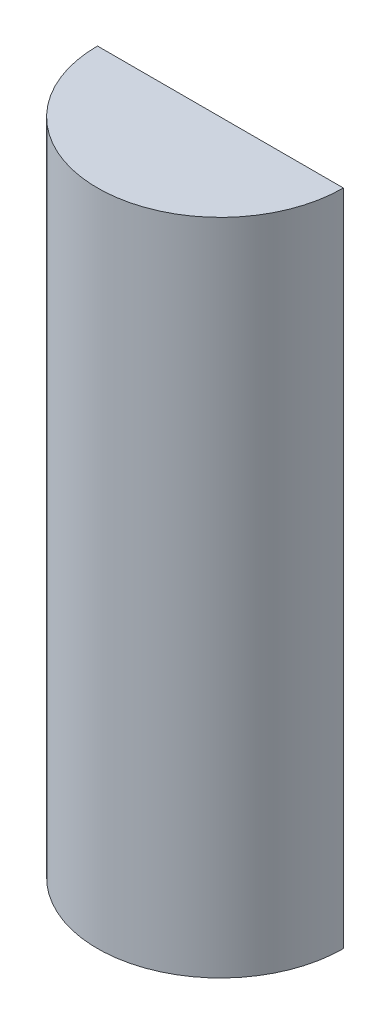
SolidWorks part; units mm, degrees
ref_plane "前视基准面" through (0, 0, 0) normal (0, 0, 1) x (1, 0, 0)
ref_plane "上视基准面" through (0, 0, 0) normal (0, 1, 0) x (1, 0, 0)
ref_plane "右视基准面" through (0, 0, 0) normal (1, 0, 0) x (0, 0, -1)
other "Configuration Table"
sketch "草图1" plane through (0, 0, 0) normal (0, 1, 0) x (1, 0, 0)
  line L0 (-5.6, 0) -> (5.6, 0)
  arc A0 (-5.6, 0) -> (5.6, 0) centre (0, 0) ccw
  dimension "D1" = 11.2
extrude "凸台-拉伸1" add sketch "草图1" along normal blind 30
